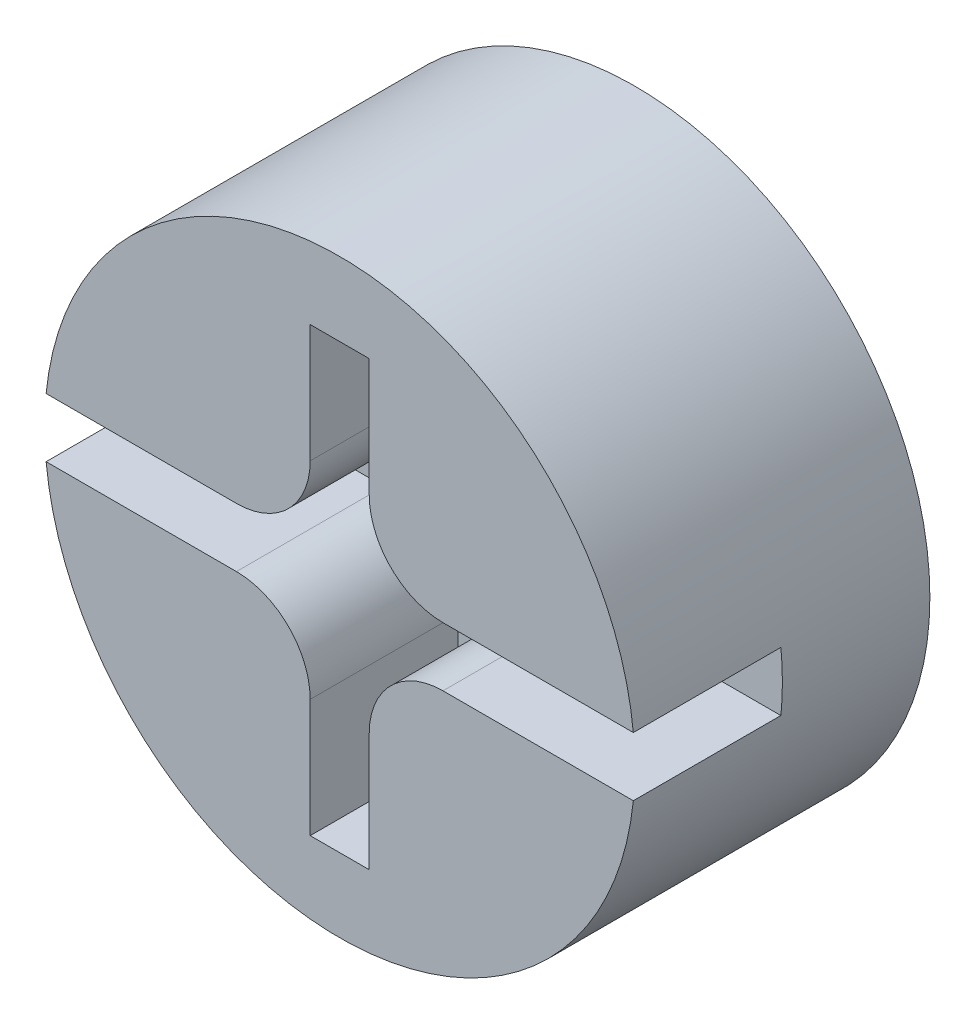
SolidWorks part; units mm, degrees
ref_plane "Спереди" through (0, 0, 0) normal (0, 0, 1) x (1, 0, 0)
ref_plane "Сверху" through (0, 0, 0) normal (0, 1, 0) x (1, 0, 0)
ref_plane "Справа" through (0, 0, 0) normal (1, 0, 0) x (0, 0, -1)
sketch "Эскиз1" plane through (0, 0, 0) normal (0, 1, 0) x (1, 0, 0)
  line L0 (2, 0) -> (0, 0)
  line L1 (0, 0) -> (0, -2)
  line L2 (0, -2) -> (2, -2)
  line L3 (2, -2) -> (2, 0)
  line L4 (0, 0) -> (0, -2) construction
revolve "Повернуть1" add sketch "Эскиз1" angle 360 about L4
sketch "Эскиз2" plane through (0, 0, 2) normal (0, 0, 1) x (1, 0, 0)
  line L0 (1.99, 0.2) -> (-1.99, 0.2)
  arc A0 (-1.99, 0.2) -> (1.99, 0.2) centre (0, 0) ccw
extrude "Вырез-Вытянуть1" cut sketch "Эскиз2" against normal blind 1
sketch "Эскиз3" plane through (0, 0.2, 0) normal (0, -1, 0) x (1, 0, 0)
  line L0 (-0.2, 1) -> (0.2, 1)
  line L1 (0.2, 1) -> (0.2, 2)
  line L2 (0.2, 2) -> (-0.2, 2)
  line L3 (-0.2, 2) -> (-0.2, 1)
extrude "Вырез-Вытянуть2" cut sketch "Эскиз3" against normal blind 1.3
sketch "Эскиз4" plane through (0, 0, 1) normal (0, 0, 1) x (1, 0, 0)
  line L0 (-1.99, -0.2) -> (1.99, -0.2)
  arc A0 (1.99, -0.2) -> (-1.99, -0.2) centre (0, 0) cw
extrude "Бобышка-Вытянуть1" add sketch "Эскиз4" along normal blind 1
sketch "Эскиз5" plane through (0, 0, 2) normal (0, 0, 1) x (1, 0, 0)
  line L0 (-0.2, -1.5) -> (0.2, -1.5)
  line L1 (0.2, -1.5) -> (0.2, -0.2)
  line L2 (0.2, -0.2) -> (-0.2, -0.2)
  line L3 (-0.2, -0.2) -> (-0.2, -1.5)
extrude "Вырез-Вытянуть3" cut sketch "Эскиз5" against normal blind 1
fillet "Скругление1" radius 0.5 4 edges at (0.2, 0.2, 1.5) (-0.2, 0.2, 1.5) (0.2, -0.2, 1.5) (-0.2, -0.2, 1.5)
